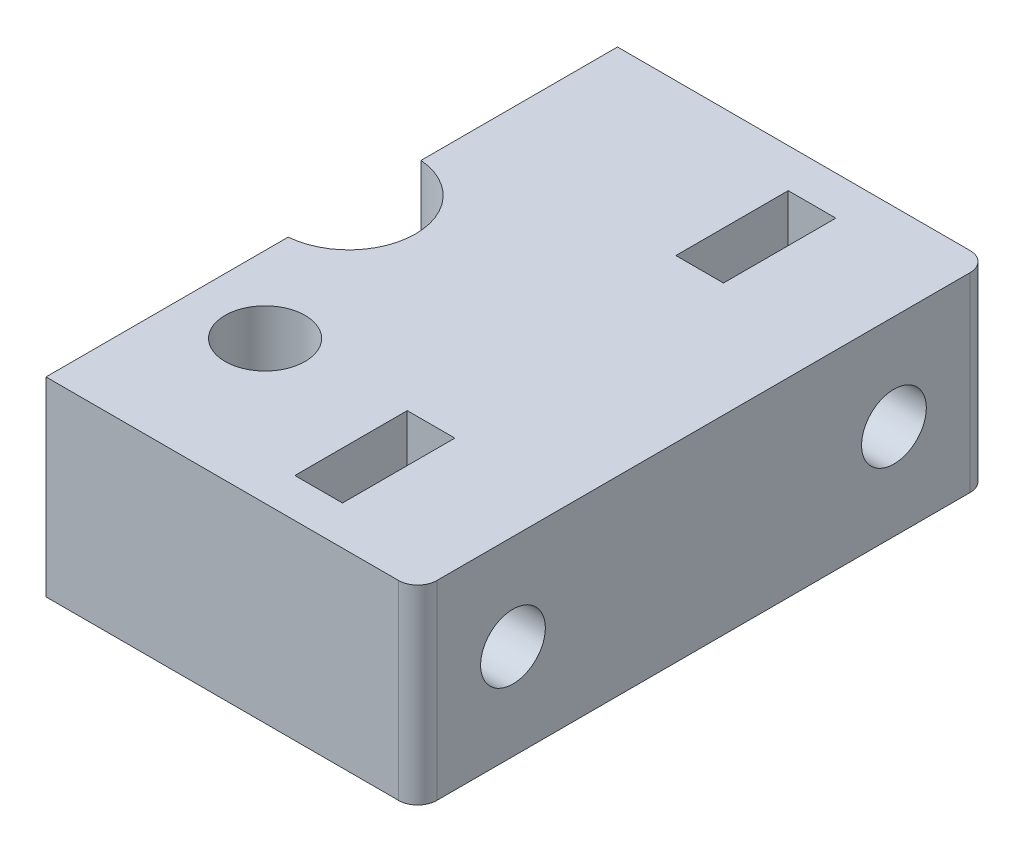
SolidWorks part; units mm, degrees
ref_plane "Front Plane" through (0, 0, 0) normal (0, 0, 1) x (1, 0, 0)
ref_plane "Top Plane" through (0, 0, 0) normal (0, 1, 0) x (1, 0, 0)
ref_plane "Right Plane" through (0, 0, 0) normal (1, 0, 0) x (0, 0, -1)
sketch "Sketch1" plane through (0, 0, 0) normal (0, 1, 0) x (1, 0, 0)
  line L1 (-29.5136, -15) -> (29.5136, -15)
  line L2 (-29.5136, -15) -> (-29.5136, 15)
  line L3 (-29.5136, 15) -> (29.5136, 15)
  line L4 (29.5136, -15) -> (29.5136, 15)
  line L5 (-29.5136, -15) -> (29.5136, 15) construction
  line L6 (-29.5136, 15) -> (29.5136, -15) construction
  point P0 (0, 0)
  dimension "D1" = 59.0272
  dimension "D2" = 30
extrude "Boss-Extrude1" add sketch "Sketch1" along normal blind 10
sketch "Sketch2" plane through (0, 10, 0) normal (0, 1, 0) x (1, 0, 0)
  line L0 (-6, -7.5) -> (14, -7.5) construction
  line L1 (29.5136, -15) -> (29.5136, 15) construction
  line L3 (4, 15) -> (4, -15) construction
  line L5 (-29.5136, -15) -> (29.5136, -15) construction
  circle A0 centre (-6, -7.5) radius 2.1
  circle A1 centre (14, -7.5) radius 2.1
  point P3 (4, -7.5)
  dimension "D1" = 4.2
  dimension "D2" = 20
  dimension "D3" = 7.5
  dimension "D4" = 25.5136
extrude "Cut-Extrude1" cut sketch "Sketch2" against normal through all
sketch "Sketch3" plane through (29.5136, 0, 0) normal (1, 0, 0) x (0, 0, -1)
  line L0 (0, 10) -> (0, 0) construction
  line L1 (-15, 10) -> (15, 10) construction
  line L2 (-15, 0) -> (15, 0) construction
  line L3 (-10, 5) -> (10, 5) construction
  circle A0 centre (-10, 5) radius 1.7
  circle A1 centre (10, 5) radius 1.7
  point P9 (0, 5)
  dimension "D2" = 3.4
  dimension "D1" = 20
extrude "Cut-Extrude2" cut sketch "Sketch3" against normal blind 12
sketch "Sketch4" plane through (-29.5136, 0, 0) normal (-1, 0, 0) x (0, 0, 1)
  line L0 (0, 10) -> (0, 0) construction
  line L3 (-10, 5) -> (10, 5) construction
  line L4 (-15, 10) -> (15, 10) construction
  circle A0 centre (-10, 5) radius 1.65
  circle A1 centre (10, 5) radius 1.65
  point P9 (0, 5)
  dimension "D2" = 3.3
  dimension "D1" = 20
extrude "Cut-Extrude3" cut sketch "Sketch4" against normal blind 12
ref_plane "Plane1" through (23.5136, 0, 0) normal (1, 0, 0) x (0, 0, -1)
ref_plane "Plane2" through (-23.5136, 0, 0) normal (-1, 0, 0) x (0, 0, 1)
sketch "Sketch5" plane through (23.5136, 0, 0) normal (1, 0, 0) x (0, 0, -1)
  line L0 (-12.95, 6.7032) -> (-12.95, 10)
  line L1 (-7.05, 6.7032) -> (-10, 8.4064) construction
  line L2 (-10, 8.4064) -> (-12.95, 6.7032) construction
  line L3 (-12.95, 6.7032) -> (-12.95, 3.2968)
  line L4 (-12.95, 3.2968) -> (-10, 1.5936)
  line L5 (-10, 1.5936) -> (-7.05, 3.2968)
  line L6 (-7.05, 3.2968) -> (-7.05, 6.7032)
  line L7 (10, 8.4064) -> (7.05, 6.7032) construction
  line L8 (7.05, 6.7032) -> (7.05, 3.2968)
  line L9 (7.05, 3.2968) -> (10, 1.5936)
  line L10 (10, 1.5936) -> (12.95, 3.2968)
  line L11 (12.95, 3.2968) -> (12.95, 6.7032)
  line L12 (12.95, 6.7032) -> (10, 8.4064) construction
  line L13 (-15, 10) -> (15, 10) construction
  line L14 (-12.95, 10) -> (-7.05, 10)
  line L15 (-7.05, 10) -> (-7.05, 6.7032)
  line L16 (7.05, 6.7032) -> (7.05, 10)
  line L17 (7.05, 10) -> (12.95, 10)
  line L18 (12.95, 10) -> (12.95, 6.7032)
  circle A0 centre (-10, 5) radius 2.95 construction
  circle A1 centre (10, 5) radius 2.95 construction
  dimension "D1" = 5.9
extrude "Cut-Extrude4" cut sketch "Sketch5" against normal blind 2.5
sketch "Sketch6" plane through (-23.5136, 0, 0) normal (-1, 0, 0) x (0, 0, 1)
  line L0 (-12.85, 6.6454) -> (-12.85, 10)
  line L1 (-7.15, 6.6454) -> (-10, 8.2909) construction
  line L2 (-10, 8.2909) -> (-12.85, 6.6454) construction
  line L3 (-12.85, 6.6454) -> (-12.85, 3.3546)
  line L4 (-12.85, 3.3546) -> (-10, 1.7091)
  line L5 (-10, 1.7091) -> (-7.15, 3.3546)
  line L6 (-7.15, 3.3546) -> (-7.15, 6.6454)
  line L7 (10, 8.2909) -> (7.15, 6.6454) construction
  line L8 (7.15, 6.6454) -> (7.15, 3.3546)
  line L9 (7.15, 3.3546) -> (10, 1.7091)
  line L10 (10, 1.7091) -> (12.85, 3.3546)
  line L11 (12.85, 3.3546) -> (12.85, 6.6454)
  line L12 (12.85, 6.6454) -> (10, 8.2909) construction
  line L14 (-12.85, 10) -> (-7.15, 10)
  line L15 (-7.15, 10) -> (-7.15, 6.6454)
  line L16 (7.15, 6.6454) -> (7.15, 10)
  line L17 (7.15, 10) -> (12.85, 10)
  line L18 (12.85, 10) -> (12.85, 6.6454)
  line L19 (-15, 10) -> (15, 10) construction
  circle A0 centre (-10, 5) radius 2.85 construction
  circle A1 centre (10, 5) radius 2.85 construction
  circle A2 centre (-10, 5) radius 1.65 construction
  circle A3 centre (-10, 5) radius 1.65 construction
  circle A5 centre (10, 5) radius 1.65 construction
  circle A6 centre (10, 5) radius 1.65 construction
  dimension "D1" = 5.7
extrude "Cut-Extrude5" cut sketch "Sketch6" against normal blind 2.3
sketch "Sketch7" plane through (0, 10, 0) normal (0, 1, 0) x (1, 0, 0)
  line L1 (-29.5136, -15) -> (29.5136, -15) construction
  line L2 (9.7, 1.2) -> (-15.7, 1.2) construction
  line L3 (-29.5136, 15) -> (-29.5136, -15) construction
  circle A0 centre (9.7, 1.2) radius 3.5
  circle A1 centre (-15.7, 1.2) radius 3.5
  dimension "D3" = 7
  dimension "D1" = 13.8136
  dimension "D2" = 16.2
  dimension "D4" = 25.4
extrude "Cut-Extrude6" cut sketch "Sketch7" against normal through all
fillet "Fillet1" radius 1 4 edges at (29.5136, 5, -15) (29.5136, 5, 15) (-29.5136, 5, -15) (-29.5136, 5, 15)
sketch "Sketch8" plane through (0, 10, 0) normal (0, 1, 0) x (1, 0, 0)
  line L1 (-29.5136, -15) -> (10, -15)
  line L2 (-28.5136, -15) -> (28.5136, -15) construction
  line L3 (10, -15) -> (10, 15)
  line L4 (-29.5136, -15) -> (-29.5136, 15)
  line L6 (-29.5136, 14) -> (-29.5136, -14) construction
  line L7 (28.5136, 15) -> (-28.5136, 15) construction
  line L8 (10, 15) -> (-29.5136, 15)
  dimension "D1" = 10
extrude "Cut-Extrude7" cut sketch "Sketch8" against normal through all
